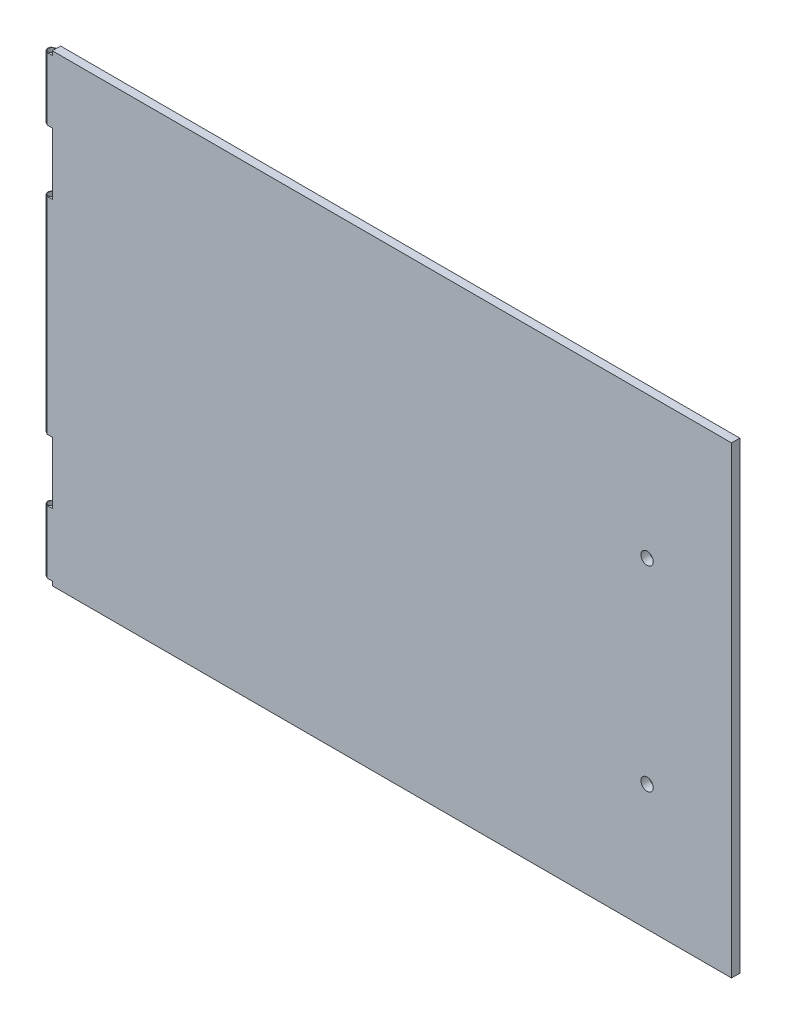
SolidWorks part; units mm, degrees
ref_plane "Front Plane" through (0, 0, 0) normal (0, 0, 1) x (1, 0, 0)
ref_plane "Top Plane" through (0, 0, 0) normal (0, 1, 0) x (1, 0, 0)
ref_plane "Right Plane" through (0, 0, 0) normal (1, 0, 0) x (0, 0, -1)
sketch "Sketch2" plane through (0, 0, 0) normal (0, 0, 1) x (1, 0, 0)
  line L1 (0, 0) -> (334, 0)
  line L2 (0, 0) -> (0, 225)
  line L3 (0, 225) -> (334, 225)
  line L4 (334, 0) -> (334, 225)
  dimension "D1" = 334
  dimension "D2" = 225
extrude "Boss-Extrude1" add sketch "Sketch2" along normal mid plane 4
sketch "Sketch3" plane through (0, 225, 0) normal (0, 1, 0) x (1, 0, 0)
  line L0 (1.75, 1.75) -> (1.75, 2)
  line L2 (334, 2) -> (0, 2) construction
  line L4 (1.75, -1.75) -> (1.75, -2)
  line L5 (334, -2) -> (0, -2) construction
  circle A0 centre (1.75, 0) radius 1.75
  circle A1 centre (1.75, 0) radius 1.5
  line M4 (334, 2) -> (0, 2)
  line M5 (0, 2) -> (0, -2)
  line M6 (0, -2) -> (334, -2)
  dimension "D1" = 3.5
  dimension "D2" = 0.25
extrude "Cut-Extrude1" cut sketch "Sketch3" against normal through all contours A0 L0 M4 M5 | A0 L4 M5 M6 | A1
sketch "Sketch4" plane through (0, 0, 2) normal (0, 0, 1) x (1, 0, 0)
  line L0 (334, 112.5) -> (0, 112.5) construction
  line L1 (334, 0) -> (334, 225) construction
  line L2 (0, 225) -> (0, 0) construction
  line L5 (4.25, 192.5) -> (0, 192.5)
  line L6 (4.25, 192.5) -> (4.25, 162.5)
  line L7 (4.25, 162.5) -> (0, 162.5)
  line L8 (0, 192.5) -> (0, 162.5)
  line L9 (0, 32.5) -> (0, 62.5)
  line L10 (4.25, 62.5) -> (0, 62.5)
  line L11 (4.25, 32.5) -> (4.25, 62.5)
  line L12 (4.25, 32.5) -> (0, 32.5)
  line L14 (3.25, 0) -> (3.25, 225) construction
  dimension "D1" = 30
  dimension "D2" = 50
  dimension "D3" = 1
extrude "Cut-Extrude2" cut sketch "Sketch4" against normal through all
sketch "Sketch5" plane through (0, 0, 2) normal (0, 0, 1) x (1, 0, 0)
  line L0 (0.25, 112.5) -> (334, 112.5) construction
  line L1 (0, 225) -> (4.25, 225)
  line L2 (0, 225) -> (0, 223)
  line L3 (0, 223) -> (4.25, 223)
  line L4 (4.25, 225) -> (4.25, 223)
  line L5 (0.25, 162.5) -> (0.25, 62.5) construction
  line L6 (334, 0) -> (334, 225) construction
  line L7 (4.25, 0) -> (4.25, 2)
  line L8 (0, 2) -> (4.25, 2)
  line L9 (0, 0) -> (0, 2)
  line L10 (0, 0) -> (4.25, 0)
  dimension "D1" = 2
  dimension "D2" = 4.25
extrude "Cut-Extrude3" cut sketch "Sketch5" against normal through all
sketch "Sketch6" plane through (0, 0, 2) normal (0, 0, 1) x (1, 0, 0)
  circle A0 centre (293, 156) radius 3
  circle A1 centre (293, 61) radius 3
  dimension "D1" = 6
  dimension "D2" = 6
extrude "Cut-Extrude4" cut sketch "Sketch6" against normal blind 10
